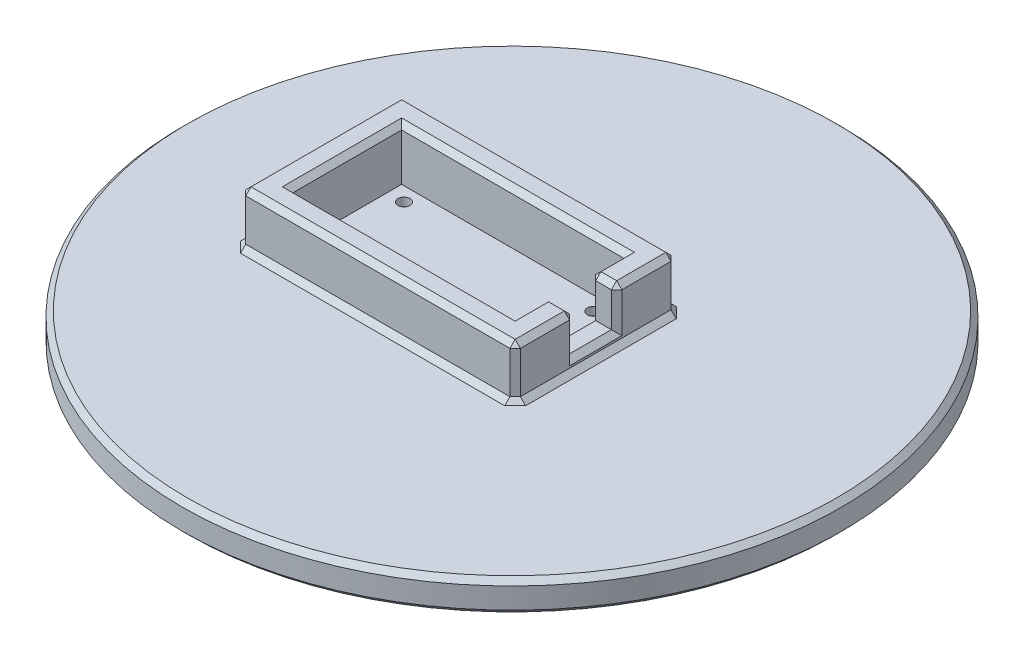
SolidWorks part; units mm, degrees
ref_plane "Front Plane" through (0, 0, 0) normal (0, 0, 1) x (1, 0, 0)
ref_plane "Top Plane" through (0, 0, 0) normal (0, 1, 0) x (1, 0, 0)
ref_plane "Right Plane" through (0, 0, 0) normal (1, 0, 0) x (0, 0, -1)
sketch "Sketch1" plane through (0, 0, 0) normal (0, 1, 0) x (1, 0, 0)
  circle A0 centre (0, 0) radius 63
  dimension "D1" = 126
extrude "Boss-Extrude1" add sketch "Sketch1" along normal blind 6
chamfer "Chamfer2" distance 1 angle 45 2 edges at (0, 0, 63) (0, 6, 63)
sketch "Sketch4" plane through (0, 6, 0) normal (0, 1, 0) x (1, 0, 0)
  line L0 (-67.9403, 0) -> (68.6768, 0) construction
  line L2 (-31.5, 10.4) -> (11, 10.4)
  line L3 (-31.5, 10.4) -> (-31.5, -10.4)
  line L4 (-31.5, -10.4) -> (11, -10.4)
  line L5 (11, 10.4) -> (11, -10.4)
  line L6 (-31.5, 10.4) -> (11, -10.4) construction
  line L7 (-31.5, -10.4) -> (11, 10.4) construction
  line L8 (-36.5, 15.4) -> (16, 15.4)
  line L9 (-36.5, 15.4) -> (-36.5, -15.4)
  line L10 (-36.5, -15.4) -> (16, -15.4)
  line L11 (16, 15.4) -> (16, -15.4)
  line L12 (-36.5, 15.4) -> (16, -15.4) construction
  line L13 (-36.5, -15.4) -> (16, 15.4) construction
  point P3 (-10.25, 0)
  point P8 (-10.25, 0)
  dimension "D1" = 11
  dimension "D2" = 5
  dimension "D3" = 5
  dimension "D4" = 20.8
  dimension "D5" = 42.5
extrude "Boss-Extrude2" add sketch "Sketch4" along normal blind 10
sketch "Sketch5" plane through (0, 16, 0) normal (0, 1, 0) x (1, 0, 0)
  line L0 (16, -15.4) -> (16, 15.4) construction
  line L1 (11, 4) -> (16, 4)
  line L2 (11, 4) -> (11, -4)
  line L3 (11, -4) -> (16, -4)
  line L4 (16, 4) -> (16, -4)
  line L5 (11, 4) -> (16, -4) construction
  line L6 (11, -4) -> (16, 4) construction
  line L7 (11, -10.4) -> (11, 10.4) construction
  point P0 (13.5, 0)
  dimension "D1" = 8
extrude "Cut-Extrude1" cut sketch "Sketch5" against normal blind 7.6
sketch "Sketch6" plane through (0, 6, 0) normal (0, 1, 0) x (1, 0, 0)
  line L0 (-10.25, 23.5674) -> (-10.25, -34.9828) construction
  line L1 (-31.5, 10.4) -> (-31.5, -10.4) construction
  line L2 (11, 4) -> (11, -4) construction
  line L3 (-43.8206, 0) -> (24.8562, 0) construction
  circle A0 centre (-28.35, 7.7) radius 1.15
  circle A1 centre (7.85, 7.7) radius 1.15
  circle A2 centre (7.85, -7.7) radius 1.15
  circle A3 centre (-28.35, -7.7) radius 1.15
  dimension "D1" = 2.3
  dimension "D2" = 36.2
  dimension "D3" = 15.4
extrude "Cut-Extrude2" cut sketch "Sketch6" against normal through all
sketch "Sketch7" plane through (0, 0, 0) normal (0, -1, 0) x (1, 0, 0)
  circle A0 centre (-28.35, 7.7) radius 2.1
  circle A1 centre (7.85, 7.7) radius 2.1
  circle A2 centre (-28.35, -7.7) radius 2.1
  circle A3 centre (7.85, -7.7) radius 2.1
  dimension "D1" = 4.2
extrude "Cut-Extrude3" cut sketch "Sketch7" against normal blind 4.41
chamfer "Chamfer3" distance 1 angle 45 26 edges at (-36.5, 11, -15.4) (-36.5, 16, 0) (-36.5, 6, 0) (-36.5, 11, 15.4) (-10.25, 6, 15.4) (16, 11, 15.4) (16, 6, 0) (-10.25, 6, -15.4) (-10.25, 16, -15.4) (16, 11, -15.4) (16, 16, -9.7) (13.5, 16, 4) (11, 12.2, 4) (11, 8.4, 0) (11, 12.2, -4) (11, 16, 7.2) (-10.25, 16, 10.4) (-31.5, 16, 0) (-10.25, 16, -10.4) (11, 16, -7.2) (13.5, 16, -4) (16, 12.2, -4) (16, 8.4, 0) (16, 12.2, 4) (-10.25, 16, 15.4) (16, 16, 9.7)
chamfer "Chamfer4" distance 0.5 angle 45 4 edges at (-28.35, 0, -9.8) (-28.35, 0, 5.6) (7.85, 0, -9.8) (7.85, 0, 5.6)
